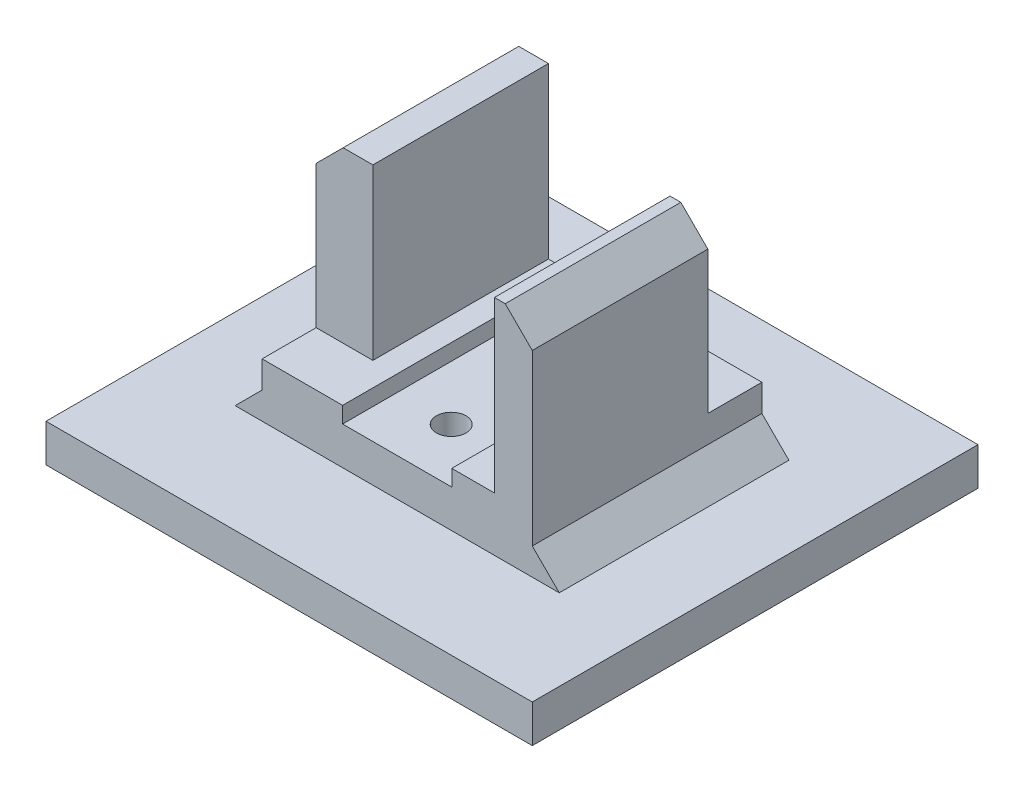
SolidWorks part; units mm, degrees
ref_plane "Front Plane" through (0, 0, 0) normal (0, 0, 1) x (1, 0, 0)
ref_plane "Top Plane" through (0, 0, 0) normal (0, 1, 0) x (1, 0, 0)
ref_plane "Right Plane" through (0, 0, 0) normal (1, 0, 0) x (0, 0, -1)
sketch "Sketch1" plane through (0, 0, 0) normal (1, 0, 0) x (0, 0, -1)
  line L1 (-25.5741, -19.2478) -> (-68.0741, -19.2478)
  line L2 (-25.5741, -19.2478) -> (-25.5741, -30.2478)
  line L3 (-25.5741, -30.2478) -> (-68.0741, -30.2478)
  line L4 (-68.0741, -19.2478) -> (-68.0741, -30.2478)
  dimension "D1" = 42.5
  dimension "D2" = 11
extrude "Boss-Extrude1" add sketch "Sketch1" along normal blind 50
sketch "Sketch2" plane through (0, 0, 0) normal (-1, 0, 0) x (0, 0, 1)
  line L0 (68.0741, -19.2478) -> (68.0741, -30.2478) construction
  line L1 (5.5741, -30.2478) -> (88.0741, -30.2478)
  line L2 (5.5741, -30.2478) -> (5.5741, -26.2478)
  line L3 (5.5741, -26.2478) -> (88.0741, -26.2478)
  line L4 (88.0741, -30.2478) -> (88.0741, -26.2478)
  line L5 (25.5741, -30.2478) -> (25.5741, -19.2478) construction
  dimension "D1" = 4
  dimension "D2" = 20
  dimension "D3" = 20
extrude "Boss-Extrude2" add sketch "Sketch2" along normal blind 20
sketch "Sketch3" plane through (0, 0, 0) normal (1, 0, 0) x (0, 0, -1)
  line L1 (-88.0741, -30.2478) -> (-5.5741, -30.2478)
  line L2 (-88.0741, -30.2478) -> (-88.0741, -26.2478)
  line L3 (-88.0741, -26.2478) -> (-5.5741, -26.2478)
  line L4 (-5.5741, -30.2478) -> (-5.5741, -26.2478)
extrude "Boss-Extrude3" add sketch "Sketch3" along normal blind 70
sketch "Sketch4" plane through (0, 0, 68.0741) normal (0, 0, 1) x (1, 0, 0)
  line L0 (50, -19.2478) -> (0, -19.2478) construction
  line L1 (10.5, -19.2478) -> (0, -19.2478)
  line L2 (10.5, -19.2478) -> (10.5, 15.0934)
  line L3 (10.5, 15.0934) -> (0, 15.0934)
  line L4 (0, -19.2478) -> (0, 15.0934)
  line L5 (0, -19.2478) -> (0, -26.2478) construction
  line L6 (50, -19.2478) -> (43, -19.2478)
  line L7 (50, -19.2478) -> (50, 15.0934)
  line L8 (50, 15.0934) -> (43, 15.0934)
  line L9 (43, -19.2478) -> (43, 15.0934)
  dimension "D1" = 10.5
  dimension "D2" = 7
extrude "Boss-Extrude4" add sketch "Sketch4" against normal up to surface (42.5 mm away) up to face at (25, -22.7478, 25.5741)
chamfer "Chamfer1" distance 5 angle 45 2 edges at (0, -26.2478, 46.8241) (50, -26.2478, 46.8241)
sketch "Sketch5" plane through (0, -30.2478, 0) normal (0, -1, 0) x (1, 0, 0)
  line L1 (-20, 5.5741) -> (70, 5.5741)
  line L2 (-20, 5.5741) -> (-20, 88.0741)
  line L3 (-20, 88.0741) -> (70, 88.0741)
  line L4 (70, 5.5741) -> (70, 88.0741)
extrude "Boss-Extrude5" add sketch "Sketch5" along normal blind 3
sketch "Sketch6" plane through (0, -19.2478, 0) normal (0, 1, 0) x (1, 0, 0)
  circle A0 centre (25, -36.0741) radius 2.75
  circle A1 centre (25, -58.0741) radius 2.75
  dimension "D1" = 5.5
  dimension "D2" = 5.5
extrude "Cut-Extrude1" cut sketch "Sketch6" against normal through all
sketch "Sketch7" plane through (0, -19.2478, 0) normal (0, 1, 0) x (1, 0, 0)
  line L0 (43, -25.5741) -> (10.5, -25.5741) construction
  line L1 (43, -68.0741) -> (35.1, -68.0741)
  line L2 (43, -68.0741) -> (43, -25.5741)
  line L3 (43, -25.5741) -> (35.1, -25.5741)
  line L4 (35.1, -68.0741) -> (35.1, -25.5741)
  line L5 (35, -68.5741) -> (35, -47.5741) construction
  line L6 (10.5, -68.0741) -> (14.9, -68.0741)
  line L7 (10.5, -68.0741) -> (10.5, -25.5741)
  line L8 (10.5, -25.5741) -> (14.9, -25.5741)
  line L9 (14.9, -68.0741) -> (14.9, -25.5741)
  line L10 (15, -68.5741) -> (15, -47.5741) construction
  dimension "D1" = 0.1
  dimension "D2" = 0.1
extrude "Boss-Extrude6" add sketch "Sketch7" along normal blind 3
chamfer "Chamfer2" distance 5 angle 45 2 edges at (50, 15.0934, 46.8241) (0, 15.0934, 46.8241)
sketch "Sketch8" plane through (0, 15.0934, 0) normal (0, 1, 0) x (1, 0, 0)
  line L0 (10.5, -25.5741) -> (10.5, -68.0741) construction
  line L1 (5, -68.0741) -> (10.5, -68.0741)
  line L2 (5, -68.0741) -> (5, -58.0741)
  line L3 (5, -58.0741) -> (10.5, -58.0741)
  line L4 (10.5, -68.0741) -> (10.5, -58.0741)
  line L5 (45, -68.0741) -> (45, -25.5741) construction
  line L6 (50, -25.5741) -> (45, -25.5741)
  line L7 (50, -25.5741) -> (50, -35.5741)
  line L8 (50, -35.5741) -> (45, -35.5741)
  line L9 (45, -25.5741) -> (45, -35.5741)
  dimension "D1" = 10
  dimension "D2" = 10
extrude "Cut-Extrude2" cut sketch "Sketch8" against normal up to surface (31.3412 mm away) up to face at (12.7, -16.2478, 46.8241)
sketch "Sketch9" plane through (0, 15.0934, 0) normal (0, 1, 0) x (1, 0, 0)
  line L0 (0, -68.0741) -> (0, -25.5741) construction
  line L1 (45, -35.5741) -> (43, -35.5741)
  line L2 (45, -35.5741) -> (45, -25.5741)
  line L3 (45, -25.5741) -> (43, -25.5741)
  line L4 (43, -35.5741) -> (43, -25.5741)
  line L5 (5, -68.0741) -> (0, -68.0741)
  line L6 (5, -68.0741) -> (5, -58.0741)
  line L7 (5, -58.0741) -> (0, -58.0741)
  line L8 (0, -68.0741) -> (0, -58.0741)
extrude "Cut-Extrude3" cut sketch "Sketch9" against normal up to surface (31.3412 mm away) up to face at (47.5, -16.2478, 30.5741)
